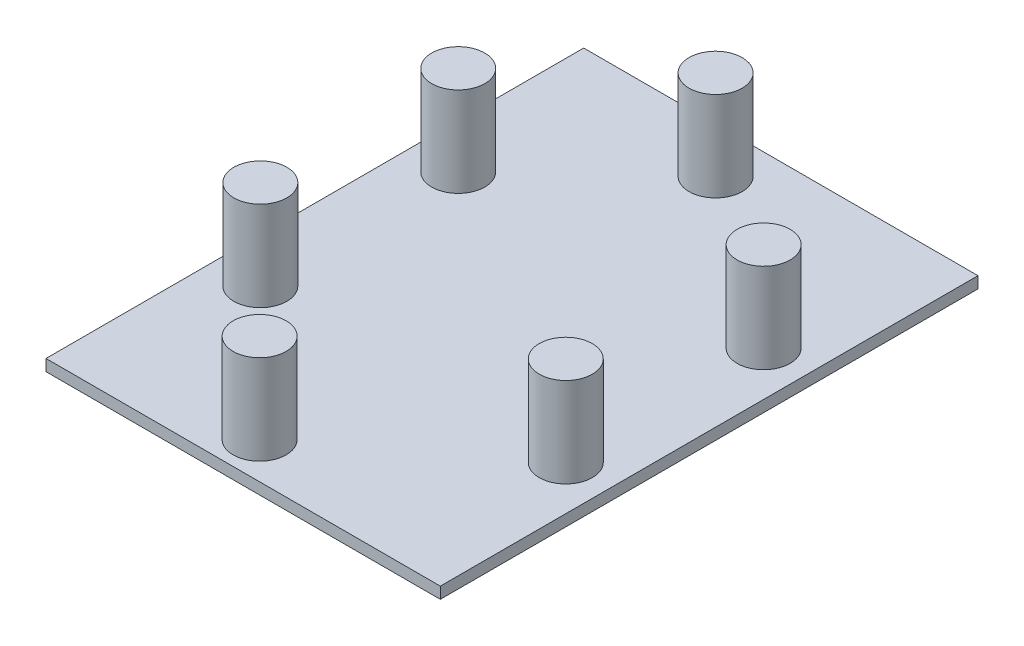
SolidWorks part; units mm, degrees
material "Copper"
ref_plane "Front Plane" through (0, 0, 0) normal (0, 0, 1) x (1, 0, 0)
ref_plane "Top Plane" through (0, 0, 0) normal (0, 1, 0) x (1, 0, 0)
ref_plane "Right Plane" through (0, 0, 0) normal (1, 0, 0) x (0, 0, -1)
sketch "Sketch1" plane through (0, 0, 0) normal (0, 1, 0) x (1, 0, 0)
  line L1 (-27.5, -37.5) -> (27.5, -37.5)
  line L2 (-27.5, -37.5) -> (-27.5, 37.5)
  line L3 (-27.5, 37.5) -> (27.5, 37.5)
  line L4 (27.5, -37.5) -> (27.5, 37.5)
  line L5 (-27.5, -37.5) -> (27.5, 37.5) construction
  line L6 (-27.5, 37.5) -> (27.5, -37.5) construction
  point P0 (0, 0)
  dimension "D1" = 75
  dimension "D2" = 55
extrude "Boss-Extrude1" add sketch "Sketch1" along normal blind 1.6 contours L2 L3 L4 L1
sketch "Sketch2" plane through (0, 1.6, 0) normal (0, 1, 0) x (1, 0, 0)
  line L0 (0, 37.5) -> (0, -37.5) construction
  line L1 (-27.5, 37.5) -> (27.5, 37.5) construction
  line L2 (-27.5, -37.5) -> (27.5, -37.5) construction
  line L3 (-27.5, 0) -> (27.5, 0) construction
  line L4 (-27.5, -37.5) -> (-27.5, 37.5) construction
  line L5 (27.5, -37.5) -> (27.5, 37.5) construction
  circle A0 centre (-2.8, -32.4) radius 3.7
  circle A1 centre (-21.3, -13.8) radius 3.7
  circle A2 centre (-21.3, 13.8) radius 3.7
  circle A3 centre (-2.8, 31.2) radius 3.7
  circle A4 centre (21.3, 13.8) radius 3.7
  circle A5 centre (21.3, -13.8) radius 3.7
  dimension "D1" = 7.4
  dimension "D2" = 50
  dimension "D3" = 35
  dimension "D4" = 71
  dimension "D5" = 34
  dimension "D6" = 10
extrude "Boss-Extrude2" add sketch "Sketch2" along normal blind 12.5
